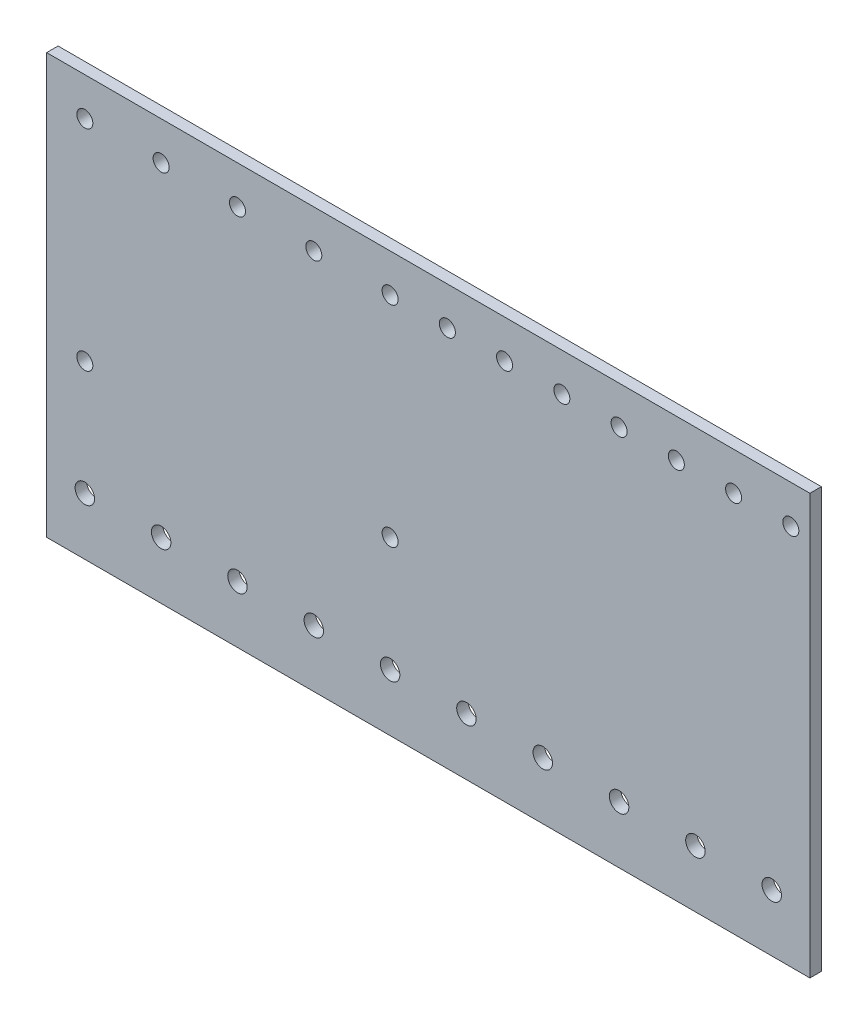
SolidWorks part; units mm, degrees
material "黑玻纤板"
ref_plane "前视基准面" through (0, 0, 0) normal (0, 0, 1) x (1, 0, 0)
ref_plane "上视基准面" through (0, 0, 0) normal (0, 1, 0) x (1, 0, 0)
ref_plane "右视基准面" through (0, 0, 0) normal (1, 0, 0) x (0, 0, -1)
sketch "草图1" plane through (0, 0, 0) normal (0, 0, 1) x (1, 0, 0)
  line L1 (-50, 65) -> (50, 65)
  line L2 (-50, 65) -> (-50, -65)
  line L3 (-50, -65) -> (50, -65)
  line L4 (50, 65) -> (50, -65)
  line L5 (-50, 65) -> (50, -65) construction
  line L6 (-50, -65) -> (50, 65) construction
  point P0 (0, 0)
  dimension "D1" = 100
  dimension "D2" = 130
extrude "凸台-拉伸1" add sketch "草图1" along normal blind 3
sketch "草图2" plane through (0, 0, 3) normal (0, 0, 1) x (1, 0, 0)
  line L0 (50, 55) -> (-50, 55) construction
  line L1 (50, -65) -> (50, 65) construction
  line L2 (-50, 65) -> (-50, -65) construction
  line L3 (50, 65) -> (-50, 65) construction
  line L4 (-40, 65) -> (-40, -65) construction
  line L5 (-50, -65) -> (50, -65) construction
  line L6 (0, 65) -> (0, -65) construction
  line L7 (40, 65) -> (40, -65) construction
  line L8 (50, 0) -> (-50, 0) construction
  line L9 (50, -55) -> (-50, -55) construction
  circle A0 centre (-40, 55) radius 2.1
  circle A1 centre (-20, 55) radius 2.1
  circle A2 centre (0, 55) radius 2.1
  circle A3 centre (20, 55) radius 2.1
  circle A4 centre (40, 55) radius 2.1
  circle A5 centre (-40, 0) radius 2.1
  circle A6 centre (-40, -55) radius 2.1
  circle A7 centre (-40, -110) radius 2.1
  circle A8 centre (-40, -165) radius 2.1
  circle A9 centre (-40, -220) radius 2.1
  circle A10 centre (-40, -275) radius 2.1
  circle A11 centre (-40, -330) radius 2.1
  circle A12 centre (-40, -385) radius 2.1
  circle A13 centre (40, -385) radius 2.1
  circle A14 centre (40, -330) radius 2.1
  circle A15 centre (40, -275) radius 2.1
  circle A16 centre (40, -220) radius 2.1
  circle A17 centre (40, -165) radius 2.1
  circle A18 centre (40, -110) radius 2.1
  circle A19 centre (40, -55) radius 2.1
  circle A20 centre (40, 0) radius 2.1
  circle A21 centre (40, 55) radius 2.1
  circle A22 centre (20, -55) radius 2.1
  circle A23 centre (0, -55) radius 2.1
  circle A24 centre (-20, -55) radius 2.1
  dimension "D3" = 4.2
  dimension "D4" = 20
  dimension "D7" = 20
  dimension "D1" = 10
  dimension "D2" = 10
  dimension "D5" = 20
  dimension "D6" = 20
  dimension "D8" = 9
extrude "切除-拉伸1" cut sketch "草图2" against normal through all contours A24 | A12 | A11 | A23 | A22 | A13 | A14 | A15 | A10 | A9 | A8 | A16 | A17 | A18 | A19 | A20 | A3 | A2 | A1 | A0 | A5 | A7 | A6 | A4
sketch "草图5" plane through (0, 0, 3) normal (0, 0, 1) x (1, 0, 0)
  line L0 (50, 65) -> (-50, 65) construction
  line L1 (50, -65) -> (150, -65)
  line L2 (50, -65) -> (50, 65)
  line L3 (50, 65) -> (150, 65)
  line L4 (150, -65) -> (150, 65)
  dimension "D1" = 100
extrude "凸台-拉伸2" add sketch "草图5" against normal up to surface (3 mm away) up to face at (42.1, 55, 0)
sketch "草图6" plane through (0, 0, 3) normal (0, 0, 1) x (1, 0, 0)
  line L0 (-40, 55) -> (150, 55) construction
  line L1 (150, -65) -> (150, 65) construction
  line L2 (150, 0) -> (-50, 0) construction
  line L3 (-50, 65) -> (-50, -65) construction
  line L4 (-40, -55) -> (150, -55) construction
  circle A0 centre (55, 55) radius 2.1
  circle A4 centre (40, 55) radius 2.1 construction
  circle A5 centre (70, 55) radius 2.1
  circle A6 centre (85, 55) radius 2.1
  circle A7 centre (100, 55) radius 2.1
  circle A8 centre (115, 55) radius 2.1
  circle A9 centre (130, 55) radius 2.1
  circle A10 centre (145, 55) radius 2.1
  circle A11 centre (145, -55) radius 2.1
  circle A12 centre (130, -55) radius 2.1
  circle A13 centre (115, -55) radius 2.1
  circle A14 centre (100, -55) radius 2.1
  circle A15 centre (85, -55) radius 2.1
  circle A16 centre (70, -55) radius 2.1
  circle A17 centre (55, -55) radius 2.1
  dimension "D1" = 15
  dimension "D2" = 7
extrude "切除-拉伸4" cut sketch "草图6" against normal through all both and the other way through all
sketch "草图7" plane through (0, 0, 0) normal (0, 0, -1) x (-1, 0, 0)
  line L0 (-150, -30) -> (50, -30) construction
  line L1 (-150, 65) -> (-150, -65) construction
  line L2 (50, 65) -> (50, -65) construction
  line L3 (-150, 65) -> (50, 65) construction
  circle A0 centre (-140, -30) radius 2.55
  circle A1 centre (-120, -30) radius 2.55
  circle A2 centre (-100, -30) radius 2.55
  circle A3 centre (-80, -30) radius 2.55
  circle A4 centre (-60, -30) radius 2.55
  circle A5 centre (-40, -30) radius 2.55
  circle A6 centre (-20, -30) radius 2.55
  circle A7 centre (0, -30) radius 2.55
  circle A8 centre (20, -30) radius 2.55
  circle A9 centre (40, -30) radius 2.55
  dimension "D2" = 10
  dimension "D3" = 5.1
  dimension "D1" = 95
  dimension "D4" = 10
extrude "切除-拉伸5" cut sketch "草图7" against normal through all both and the other way through all
sketch "草图8" plane through (0, 0, 0) normal (0, 0, -1) x (-1, 0, 0)
  line L0 (-150, 65) -> (-150, -65) construction
  line L1 (-150, -45) -> (50, -45)
  line L2 (-150, -45) -> (-150, -65)
  line L3 (-150, -65) -> (50, -65)
  line L4 (50, -45) -> (50, -65)
  dimension "D1" = 20
extrude "切除-拉伸6" cut sketch "草图8" against normal through all both and the other way through all
